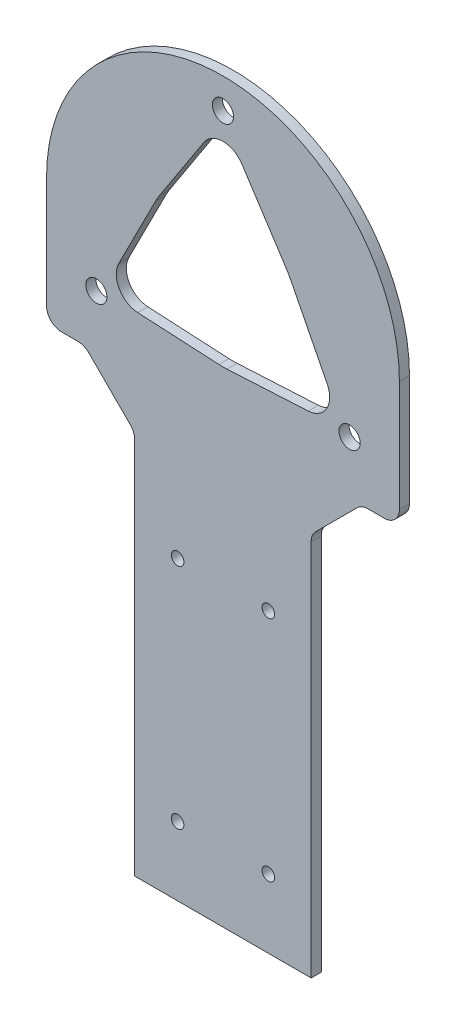
SolidWorks part; units mm, degrees
material "A-玻璃纤维"
ref_plane "前视基准面" through (0, 0, 0) normal (0, 0, 1) x (1, 0, 0)
ref_plane "上视基准面" through (0, 0, 0) normal (0, 1, 0) x (1, 0, 0)
ref_plane "右视基准面" through (0, 0, 0) normal (1, 0, 0) x (0, 0, -1)
sketch "草图1" plane through (0, 0, 0) normal (0, 0, 1) x (1, 0, 0)
  line L0 (-33.9411, 25.0103) -> (-33.9411, 3.0103)
  line L1 (-30.9411, 0.0103) -> (-27.6838, 0.0103)
  line L2 (-25.5625, -0.8684) -> (-17.3198, -9.111)
  line L3 (-16.4411, -11.2323) -> (-16.4411, -59.2162)
  line L4 (-16.4411, -59.2162) -> (18.5589, -59.2162)
  line L5 (18.5589, -59.2162) -> (18.5589, -11.2323)
  line L6 (19.4375, -9.111) -> (27.6802, -0.8684)
  line L7 (29.8015, 0.0103) -> (33.0589, 0.0103)
  line L8 (36.0589, 3.0103) -> (36.0589, 25.0103)
  line L9 (13.631, 33.1921) -> (4.8305, 46.7149)
  line L10 (21.7414, 17.4244) -> (14.4306, 31.8072)
  line L11 (1.8585, 10.0316) -> (17.9697, 10.8917)
  line L12 (-15.852, 10.8917) -> (0.2593, 10.0316)
  line L13 (-12.3129, 31.8072) -> (-19.6236, 17.4244)
  line L14 (-2.7128, 46.7149) -> (-11.5132, 33.1921)
  circle A0 centre (26.1736, 10.5103) radius 2.1
  circle A1 centre (-24.0559, 10.5103) radius 2.1
  arc A2 (-33.9411, 3.0103) -> (-30.9411, 0.0103) centre (-30.9411, 3.0103) ccw
  arc A3 (-25.5625, -0.8684) -> (-27.6838, 0.0103) centre (-27.6838, -2.9897) ccw
  arc A4 (-16.4411, -11.2323) -> (-17.3198, -9.111) centre (-19.4411, -11.2323) ccw
  arc A5 (19.4375, -9.111) -> (18.5589, -11.2323) centre (21.5589, -11.2323) ccw
  arc A6 (29.8015, 0.0103) -> (27.6802, -0.8684) centre (29.8015, -2.9897) ccw
  arc A7 (33.0589, 0.0103) -> (36.0589, 3.0103) centre (33.0589, 3.0103) ccw
  arc A8 (36.0589, 25.0103) -> (-33.9411, 25.0103) centre (1.0589, 25.0103) ccw
  arc A9 (4.8305, 46.7149) -> (-2.7128, 46.7149) centre (1.0589, 44.2603) ccw
  arc A10 (14.4306, 31.8072) -> (13.631, 33.1921) centre (1.0589, 25.0103) ccw
  arc A11 (17.9697, 10.8917) -> (21.7414, 17.4244) centre (17.7299, 15.3853) ccw
  arc A12 (0.2593, 10.0316) -> (1.8585, 10.0316) centre (1.0589, 25.0103) ccw
  arc A13 (-19.6236, 17.4244) -> (-15.852, 10.8917) centre (-15.6121, 15.3853) ccw
  arc A14 (-11.5132, 33.1921) -> (-12.3129, 31.8072) centre (1.0589, 25.0103) ccw
  circle A15 centre (1.0589, 54.0103) radius 2.1
extrude "凸台-拉伸1" add sketch "草图1" along normal blind 2
sketch "草图2" plane through (0, -59.2162, 0) normal (0, -1, 0) x (1, 0, 0)
  line L4 (-16.4411, 0) -> (18.5589, 0)
  line L5 (18.5589, 0) -> (18.5589, 2)
  line L6 (18.5589, 2) -> (-16.4411, 2)
  line L7 (-16.4411, 2) -> (-16.4411, 0)
  line L8 (-16.4411, 0) -> (18.5589, 0)
  line L9 (18.5589, 0) -> (18.5589, 2)
  line L10 (18.5589, 2) -> (-16.4411, 2)
  line L11 (-16.4411, 2) -> (-16.4411, 0)
  dimension "D1" = 0
extrude "凸台-拉伸2" add sketch "草图2" along normal blind 30
sketch "草图3" plane through (0, 0, 2) normal (0, 0, 1) x (1, 0, 0)
  line L0 (-16.4411, -11.2323) -> (-16.4411, -89.2162) construction
  line L1 (18.5589, -89.2162) -> (-16.4411, -89.2162) construction
  circle A0 centre (-11.4411, -73.2162) radius 1.3
  circle A1 centre (13.5589, -73.2162) radius 1.3
  circle A2 centre (13.5589, -46.2162) radius 1.3
  circle A3 centre (-11.4411, -46.2162) radius 1.3
  dimension "D1" = 2.6
  dimension "D2" = 5
  dimension "D3" = 16
  dimension "D6" = 27
  dimension "D4" = 2
  dimension "D5" = 2
extrude "切除-拉伸1" [suppressed] cut sketch "草图3" against normal blind 10
sketch "草图4" plane through (0, 0, 2) normal (0, 0, 1) x (1, 0, 0)
  line L1 (-16.4411, -89.2162) -> (18.5589, -89.2162)
  line L2 (-16.4411, -89.2162) -> (-16.4411, -86.2162)
  line L3 (-16.4411, -86.2162) -> (18.5589, -86.2162)
  line L4 (18.5589, -89.2162) -> (18.5589, -86.2162)
  line L5 (18.5589, -89.2162) -> (18.5589, -11.2323) construction
  dimension "D1" = 3
  dimension "D2" = 35
extrude "切除-拉伸2" cut sketch "草图4" against normal blind 10
sketch "草图5" plane through (0, 0, 2) normal (0, 0, 1) x (1, 0, 0)
  line L0 (18.5589, -86.2162) -> (-16.4411, -86.2162) construction
  line L1 (10.0589, -72.5888) -> (-7.9411, -72.5888) construction
  line L2 (10.0589, -72.5888) -> (10.0589, -27.3888) construction
  line L3 (10.0589, -27.3888) -> (-7.9411, -27.3888) construction
  line L4 (-7.9411, -72.5888) -> (-7.9411, -27.3888) construction
  line L5 (10.0589, -72.5888) -> (-7.9411, -27.3888) construction
  line L6 (10.0589, -27.3888) -> (-7.9411, -72.5888) construction
  circle A0 centre (10.0589, -27.3888) radius 1.25
  circle A1 centre (-7.9411, -27.3888) radius 1.25
  circle A2 centre (-7.9411, -72.5888) radius 1.25
  circle A3 centre (10.0589, -72.5888) radius 1.25
  point P0 (1.0589, -49.9888)
  point P13 (1.0589, -86.2162)
  dimension "D4" = 2.5
  dimension "D5" = 2.5
  dimension "D6" = 2.5
  dimension "D7" = 2.5
  dimension "D1" = 45.2
  dimension "D2" = 18
  dimension "D3" = 50
extrude "切除-拉伸3" cut sketch "草图5" against normal blind 10
